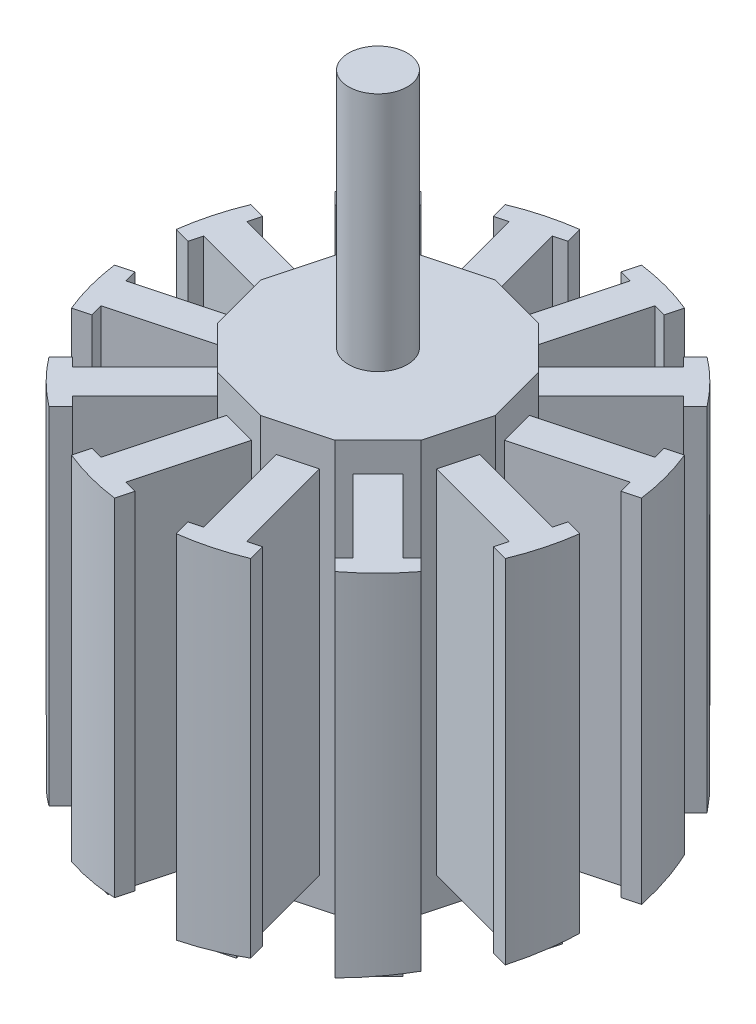
SolidWorks part; units mm, degrees
material "合金钢"
ref_plane "前视基准面" through (0, 0, 0) normal (0, 0, 1) x (1, 0, 0)
ref_plane "上视基准面" through (0, 0, 0) normal (0, 1, 0) x (1, 0, 0)
ref_plane "右视基准面" through (0, 0, 0) normal (1, 0, 0) x (0, 0, -1)
sketch "草图1" plane through (0, 0, 0) normal (0, 1, 0) x (1, 0, 0)
  circle A0 centre (0, 0) radius 1
  dimension "D1" = 2
extrude "凸台-拉伸1" add sketch "草图1" along normal blind 20
sketch "草图4" plane through (0, 20, 0) normal (0, 1, 0) x (1, 0, 0)
  line L1 (4, 0) -> (3.4641, 2)
  line L2 (3.4641, 2) -> (2, 3.4641)
  line L3 (2, 3.4641) -> (0, 4)
  line L4 (0, 4) -> (-2, 3.4641)
  line L5 (-2, 3.4641) -> (-3.4641, 2)
  line L6 (-3.4641, 2) -> (-4, 0)
  line L7 (-4, 0) -> (-3.4641, -2)
  line L8 (-3.4641, -2) -> (-2, -3.4641)
  line L9 (-2, -3.4641) -> (0, -4)
  line L10 (0, -4) -> (2, -3.4641)
  line L11 (2, -3.4641) -> (3.4641, -2)
  line L12 (3.4641, -2) -> (4, 0)
  circle A0 centre (0, 0) radius 4 construction
  dimension "D1" = 8
extrude "凸台-拉伸3" add sketch "草图4" against normal blind 14 from offset 8.2 contours L6 L7 L8 L9 L10 L11 L12 L1 L2 L3 L4 L5 offset against normal yes
sketch "草图5" plane through (0, 11.8, 0) normal (0, 1, 0) x (1, 0, 0)
  line L0 (0, 0) -> (-6.6022, 1.769) construction
  line L7 (-3.4641, 2) -> (-4, 0) construction
sketch "草图6" plane through (-3.7321, 0, -1) normal (-0.9659, 0, -0.2588) x (-0.2588, 0, 0.9659)
  line L0 (-1.0353, 11.8) -> (1.0353, 11.8) construction
  line L1 (-0.6, -1.2) -> (0.6, -1.2)
  line L2 (-0.6, -1.2) -> (-0.6, 10.8)
  line L3 (-0.6, 10.8) -> (0.6, 10.8)
  line L4 (0.6, -1.2) -> (0.6, 10.8)
  line L5 (-0.6, -1.2) -> (0.6, 10.8) construction
  line L6 (-0.6, 10.8) -> (0.6, -1.2) construction
  point P0 (0, 4.8)
  dimension "D1" = 7
  dimension "D2" = 1.2
  dimension "D3" = 12
extrude "凸台-拉伸4" add sketch "草图6" along normal blind 4
sketch "草图7" plane through (-7.5958, 0, -2.0353) normal (-0.9659, 0, -0.2588) x (-0.2588, 0, 0.9659)
  line L0 (0.6, 10.8) -> (-0.6, 10.8) construction
  line L12 (1.0353, 10.8) -> (-1.0353, 10.8)
  line L13 (-1.0353, 10.8) -> (-1.0353, -1.2)
  line L14 (-1.0353, -1.2) -> (1.0353, -1)
  line L15 (1.0353, -1) -> (1.0353, 10.8)
  dimension "D1" = 12
  dimension "D2" = 2.0706
  dimension "D3" = 0
extrude "凸台-拉伸5" add sketch "草图7" against normal blind 0.5 and the other way blind 1
pattern_circular "阵列(圆周)1" count 12 over 360 about axis through (0, 0, 0) along (0, 1, 0) of "凸台-拉伸5", "凸台-拉伸4"
sketch "草图12" plane through (0, 11.8, 0) normal (0, 1, 0) x (1, 0, 0)
  circle A0 centre (0, 0) radius 8
  dimension "D1" = 16
extrude "切除-拉伸2" cut sketch "草图12" against normal through all flip side to cut
